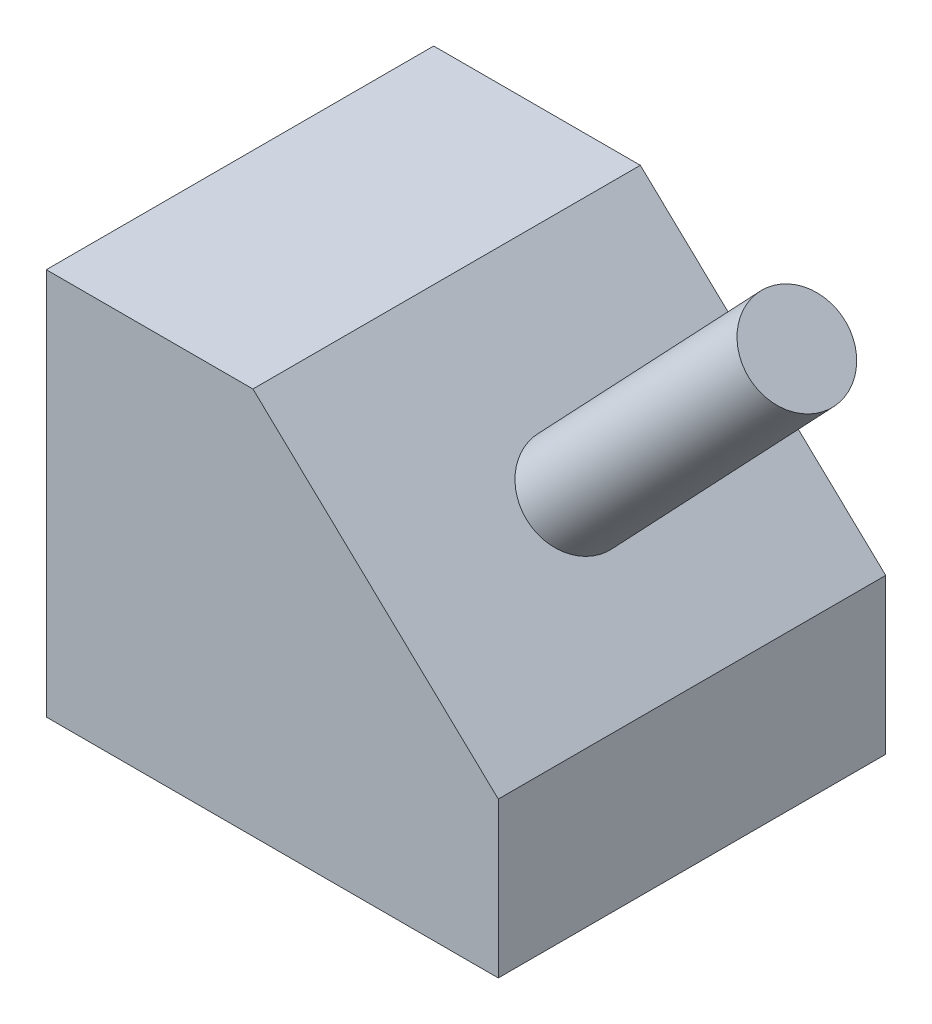
SolidWorks part; units mm, degrees
ref_plane "前基準面" through (0, 0, 0) normal (0, 0, 1) x (1, 0, 0)
ref_plane "上基準面" through (0, 0, 0) normal (0, 1, 0) x (1, 0, 0)
ref_plane "右基準面" through (0, 0, 0) normal (1, 0, 0) x (0, 0, -1)
sketch "草圖1" plane through (0, 0, 0) normal (0, 0, 1) x (1, 0, 0)
  line L0 (0, 0) -> (70, 0)
  line L1 (70, 0) -> (70, 24)
  line L2 (70, 24) -> (32, 60)
  line L3 (32, 60) -> (0, 60)
  line L4 (0, 60) -> (0, 0)
  dimension "D1" = 60
  dimension "D2" = 70
  dimension "D3" = 24
  dimension "D4" = 32
extrude "填料-伸長1" add sketch "草圖1" along normal blind 60
sketch "草圖2" plane through (45.092, 47.5971, 0) normal (0.6877, 0.726, 0) x (0.726, -0.6877, 0)
  line L0 (34.3108, 0) -> (-18.0342, 0) construction
  line L2 (34.3108, -60) -> (34.3108, 0) construction
  circle A0 centre (9.3108, -30) radius 7.5
  point P6 (34.3108, -30.2275)
  dimension "D3" = 15
  dimension "D1" = 30
  dimension "D2" = 25
extrude "填料-伸長2" add sketch "草圖2" along normal blind 50
